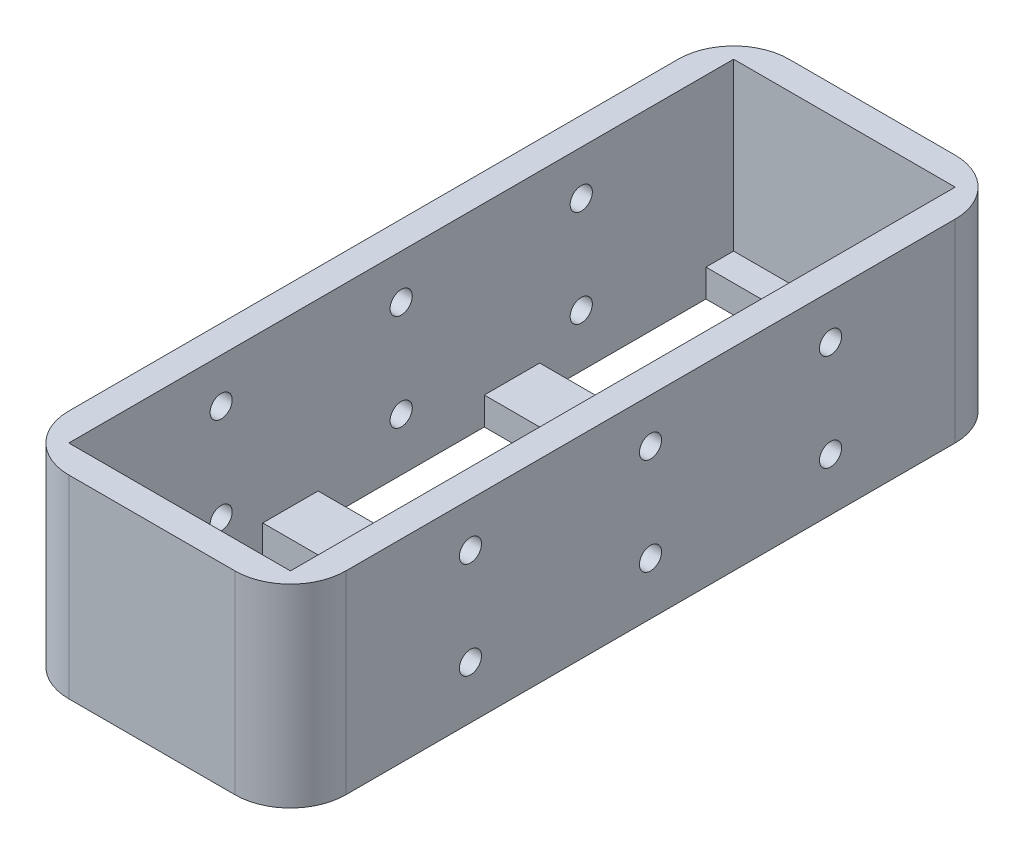
SolidWorks part; units mm, degrees
ref_plane "Front Plane" through (0, 0, 0) normal (0, 0, 1) x (1, 0, 0)
ref_plane "Top Plane" through (0, 0, 0) normal (0, 1, 0) x (1, 0, 0)
ref_plane "Right Plane" through (0, 0, 0) normal (1, 0, 0) x (0, 0, -1)
sketch "Sketch1" plane through (0, 0, 0) normal (0, 1, 0) x (1, 0, 0)
  line L0 (-25.4, -31.75) -> (25.4, -31.75)
  line L1 (-31.75, -82.55) -> (31.75, -82.55)
  line L2 (-31.75, -82.55) -> (-31.75, 82.55)
  line L3 (-31.75, 82.55) -> (31.75, 82.55)
  line L4 (31.75, -82.55) -> (31.75, 82.55)
  line L5 (-31.75, -82.55) -> (31.75, 82.55) construction
  line L6 (-31.75, 82.55) -> (31.75, -82.55) construction
  line L7 (-25.4, -19.05) -> (25.4, -19.05)
  line L8 (-25.4, 69.85) -> (25.4, 69.85)
  line L9 (25.4, -19.05) -> (25.4, 19.05)
  line L10 (-25.4, 19.05) -> (25.4, 19.05)
  line L11 (25.4, 31.75) -> (-25.4, 31.75)
  line L12 (25.4, -69.85) -> (25.4, -31.75)
  line L13 (-25.4, -69.85) -> (-25.4, -31.75)
  line L14 (-25.4, -69.85) -> (25.4, -69.85)
  line L15 (25.4, 31.75) -> (25.4, 82.55)
  line L16 (-25.4, 31.75) -> (-25.4, 69.85)
  line L17 (-25.4, -19.05) -> (-25.4, 19.05)
  point P0 (0, 0)
  dimension "D1" = 63.5
  dimension "D2" = 165.1
  dimension "D3" = 38.1
  dimension "D4" = 12.7
  dimension "D5" = 12.7
  dimension "D6" = 6.35
  dimension "D7" = 6.35
  dimension "D8" = 12.7
  dimension "D9" = 38.1
  dimension "D10" = 38.1
extrude "Mount Base" add sketch "Sketch1" along normal blind 6.35
sketch "Sketch5" plane through (0, 6.35, 0) normal (0, 1, 0) x (-1, 0, 0)
  line L0 (31.75, 82.55) -> (-31.75, 82.55) construction
  line L1 (-25.4, -76.2) -> (25.4, -76.2)
  line L2 (-25.4, -76.2) -> (-25.4, 76.2)
  line L3 (-25.4, 76.2) -> (25.4, 76.2)
  line L4 (25.4, -76.2) -> (25.4, 76.2)
  line L5 (-25.4, -76.2) -> (25.4, 76.2) construction
  line L6 (-25.4, 76.2) -> (25.4, -76.2) construction
  line L7 (31.75, 82.55) -> (31.75, -82.55) construction
  line L8 (31.75, -82.55) -> (-31.75, -82.55) construction
  line L9 (31.75, 82.55) -> (-31.75, 82.55)
  line L10 (31.75, 82.55) -> (31.75, -82.55)
  line L11 (31.75, -82.55) -> (-31.75, -82.55)
  point P0 (0, 0)
  line M1 (-31.75, 82.55) -> (-31.75, -82.55)
  line M2 (-31.75, -82.55) -> (31.75, -82.55)
  line M3 (31.75, -82.55) -> (31.75, 82.55)
  line M4 (31.75, 82.55) -> (-31.75, 82.55)
  line M6 (25.4, -31.75) -> (25.4, -69.85)
  line M8 (-25.4, -69.85) -> (-25.4, -31.75)
  line M10 (25.4, 69.85) -> (25.4, 31.75)
  line M12 (-25.4, 31.75) -> (-25.4, 69.85)
  line M14 (25.4, 19.05) -> (25.4, -19.05)
  line M16 (-25.4, -19.05) -> (-25.4, 19.05)
  dimension "D1" = 50.8
  dimension "D2" = 152.4
extrude "Boss-Extrude2" add sketch "Sketch5" along normal blind 38.1 contours L4 L1 L2 L3 M4 M1 M2 M3 M8 M16 M12 M10 M14 M6
sketch "Sketch4" plane through (31.75, 0, 0) normal (1, 0, 0) x (0, 0, -1)
  line L0 (0, 0) -> (0, 44.45) construction
  line L2 (41.275, 22.225) -> (41.275, 44.45) construction
  line L3 (-82.55, 22.225) -> (-41.275, 22.225) construction
  line L4 (0, 22.225) -> (41.275, 22.225) construction
  line L5 (-82.55, 44.45) -> (-82.55, 0) construction
  line L6 (41.275, 22.225) -> (41.275, 0) construction
  line L7 (41.275, 22.225) -> (82.55, 22.225) construction
  line L8 (-41.275, 22.225) -> (-41.275, 44.45) construction
  line L9 (-41.275, 22.225) -> (0, 22.225) construction
  line L10 (-82.55, 44.45) -> (82.55, 44.45) construction
  line L11 (82.55, 44.45) -> (82.55, 0) construction
  line L16 (-41.275, 22.225) -> (-41.275, 0) construction
  circle A0 centre (0, 34.29) radius 2.54
  circle A1 centre (41.275, 34.29) radius 2.54
  circle A2 centre (-41.275, 34.29) radius 2.54
  circle A3 centre (-41.275, 12.065) radius 2.54
  circle A4 centre (41.275, 12.065) radius 2.54
  circle A5 centre (0, 12.065) radius 2.54
  dimension "D1" = 5.08
  dimension "D2" = 10.16
  dimension "D3" = 10.16
extrude "Cut-Extrude1" cut sketch "Sketch4" against normal through all
fillet "Outside Vertices" radius 12.7 4 edges at (-31.75, 22.225, -82.55) (31.75, 22.225, -82.55) (-31.75, 22.225, 82.55) (31.75, 22.225, 82.55)
